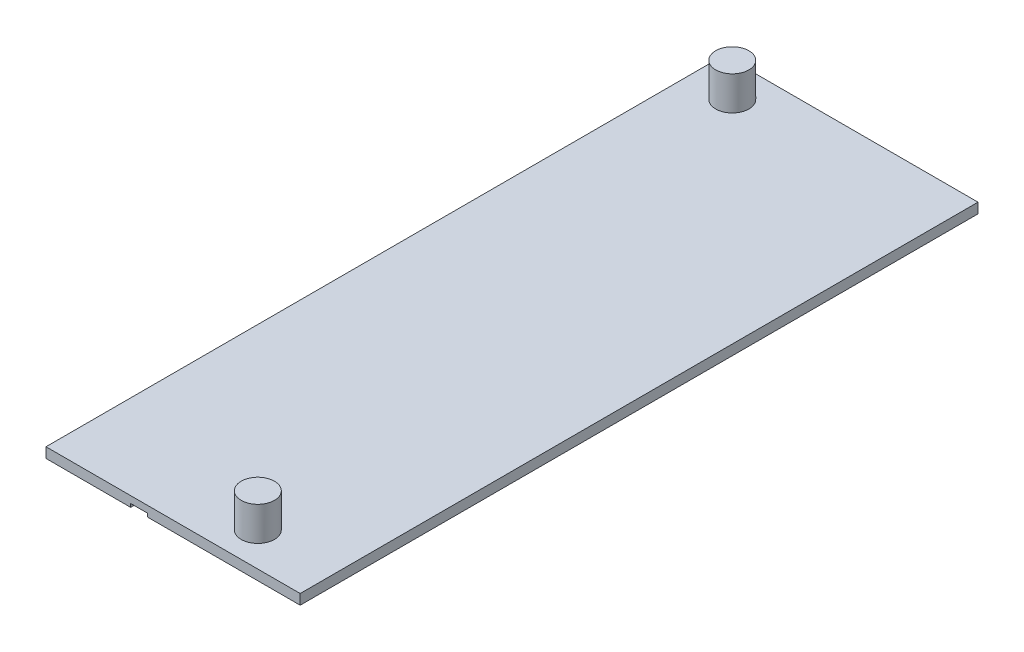
SolidWorks part; units mm, degrees
ref_plane "Front Plane" through (0, 0, 0) normal (0, 0, 1) x (1, 0, 0)
ref_plane "Top Plane" through (0, 0, 0) normal (0, 1, 0) x (1, 0, 0)
ref_plane "Right Plane" through (0, 0, 0) normal (1, 0, 0) x (0, 0, -1)
sketch "Sketch1" plane through (0, 0, 0) normal (0, 0, 1) x (1, 0, 0)
  line L1 (0, 0) -> (75, 0)
  line L2 (0, 0) -> (0, 3)
  line L3 (0, 3) -> (75, 3)
  line L4 (75, 0) -> (75, 3)
  dimension "D1" = 3
  dimension "D2" = 75
extrude "Boss-Extrude1" add sketch "Sketch1" along normal blind 200
sketch "Sketch2" plane through (0, 3, 0) normal (0, 1, 0) x (1, 0, 0)
  line L1 (75, 0) -> (-150, 0)
  line L2 (75, 0) -> (75, -200)
  line L3 (75, -200) -> (-150, -200)
  line L4 (-150, 0) -> (-150, -200)
  line L5 (62.5, -200) -> (-137.5, -200)
  line L6 (62.5, -200) -> (62.5, 0)
  line L7 (62.5, 0) -> (-137.5, 0)
  line L8 (-137.5, -200) -> (-137.5, 0)
  circle A0 centre (52.5, -190) radius 4.9
  circle A1 centre (12.5, -10) radius 4.9
  dimension "D4" = 10
  dimension "D5" = 10
  dimension "D6" = 9.8
  dimension "D7" = 9.8
  dimension "D8" = 10
  dimension "D9" = 40
  dimension "D1" = 225
  dimension "D2" = 12.5
  dimension "D3" = 12.5
extrude "Boss-Extrude2" add sketch "Sketch2" along normal blind 10 contours A1 | A0
sketch "Sketch3" plane through (0, 0, 0) normal (0, -1, 0) x (1, 0, 0)
  line L1 (4, 43) -> (11, 43)
  line L2 (4, 43) -> (4, 10)
  line L3 (4, 10) -> (11, 10)
  line L4 (11, 43) -> (11, 10)
  line L5 (4, 47) -> (11, 47)
  line L6 (4, 47) -> (4, 80)
  line L7 (4, 80) -> (11, 80)
  line L8 (11, 47) -> (11, 80)
  line L40 (0, 200) -> (75, 200) construction
  line L41 (25, 150) -> (30, 150)
  line L42 (25, 150) -> (25, 120)
  line L43 (25, 120) -> (30, 120)
  line L44 (0, 200) -> (0, 0) construction
  line L45 (19, 43) -> (26, 43)
  line L46 (19, 43) -> (19, 10)
  line L47 (19, 10) -> (26, 10)
  line L48 (26, 43) -> (26, 10)
  line L49 (19, 47) -> (26, 47)
  line L50 (19, 47) -> (19, 80)
  line L51 (19, 80) -> (26, 80)
  line L52 (26, 47) -> (26, 80)
  line L53 (34, 43) -> (41, 43)
  line L54 (34, 43) -> (34, 10)
  line L55 (34, 10) -> (41, 10)
  line L56 (41, 43) -> (41, 10)
  line L57 (34, 47) -> (41, 47)
  line L58 (34, 47) -> (34, 80)
  line L59 (34, 80) -> (41, 80)
  line L60 (41, 47) -> (41, 80)
  line L61 (49, 43) -> (56, 43)
  line L62 (49, 43) -> (49, 10)
  line L63 (49, 10) -> (56, 10)
  line L64 (56, 43) -> (56, 10)
  line L65 (49, 47) -> (56, 47)
  line L66 (49, 47) -> (49, 80)
  line L67 (49, 80) -> (56, 80)
  line L68 (56, 47) -> (56, 80)
  line L69 (64, 43) -> (71, 43)
  line L70 (64, 43) -> (64, 10)
  line L71 (64, 10) -> (71, 10)
  line L72 (71, 43) -> (71, 10)
  line L73 (64, 47) -> (71, 47)
  line L74 (64, 47) -> (64, 80)
  line L75 (64, 80) -> (71, 80)
  line L76 (71, 47) -> (71, 80)
  line L77 (30, 150) -> (30, 120)
  line L78 (0, 0) -> (75, 0) construction
  line L79 (75, 200) -> (75, 0) construction
  line L80 (25, 200) -> (30, 200)
  line L81 (25, 200) -> (25, 170)
  line L82 (25, 170) -> (30, 170)
  line L83 (30, 200) -> (30, 170)
  point P48 (27.5, 170)
  dimension "D1" = 70
  dimension "D2" = 33
  dimension "D3" = 33
  dimension "D4" = 7
  dimension "D5" = 7
  dimension "D7" = 4
  dimension "D6" = 4
  dimension "D9" = 10
  dimension "D10" = 47.5
  dimension "D11" = 30
  dimension "D12" = 5
  dimension "D8" = 5
  dimension "D13" = 2
extrude "Cut-Extrude1" cut sketch "Sketch3" against normal blind 1
